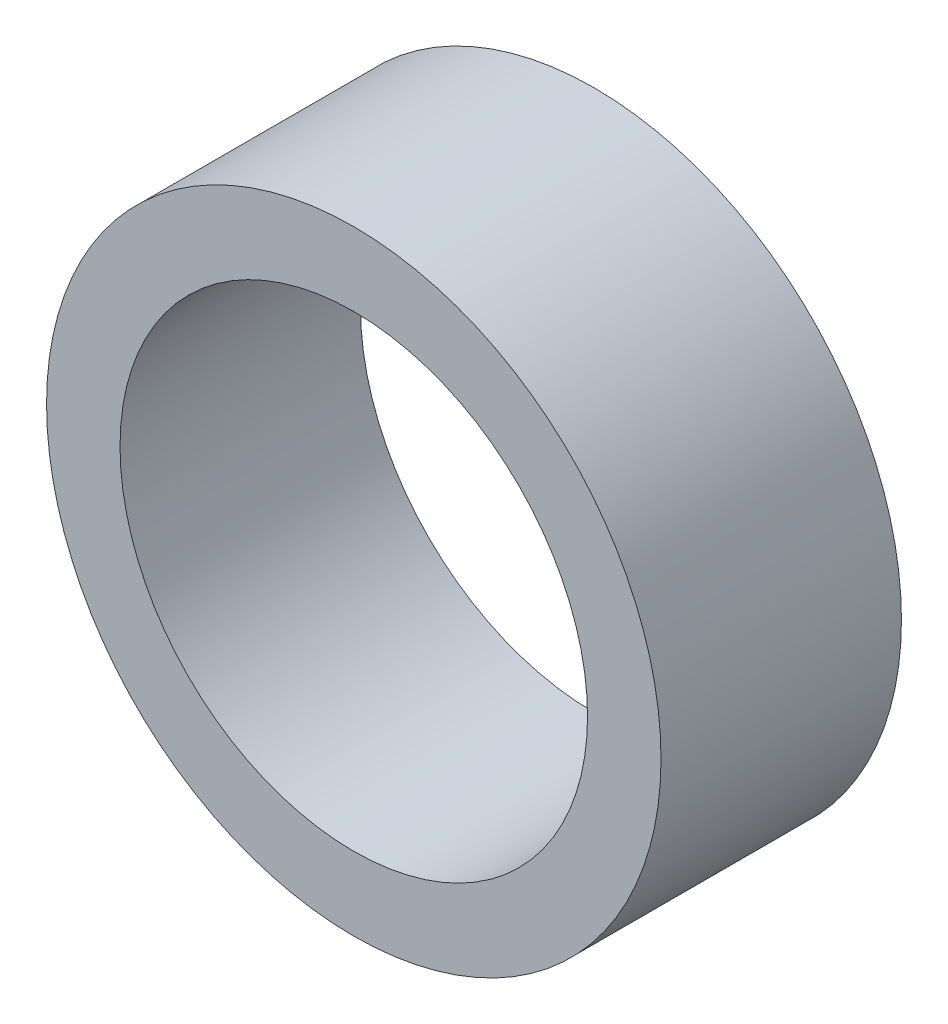
SolidWorks part; units mm, degrees
ref_plane "前视基准面" through (0, 0, 0) normal (0, 0, 1) x (1, 0, 0)
ref_plane "上视基准面" through (0, 0, 0) normal (0, 1, 0) x (1, 0, 0)
ref_plane "右视基准面" through (0, 0, 0) normal (1, 0, 0) x (0, 0, -1)
sketch "草图1" plane through (0, 0, 0) normal (0, 0, 1) x (1, 0, 0)
  circle A0 centre (0, 0) radius 11.5
  circle A1 centre (0, 0) radius 8.75
  dimension "D1" = 23
  dimension "D2" = 17.5
extrude "凸台-拉伸1" add sketch "草图1" along normal blind 9
